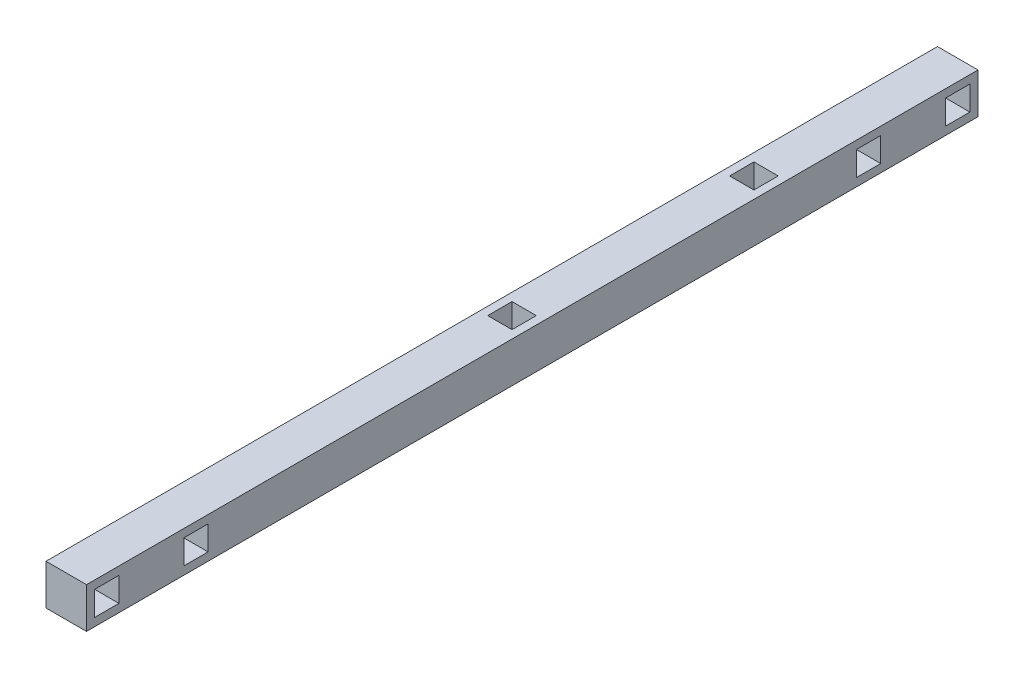
SolidWorks part; units mm, degrees
ref_plane "Front Plane" through (0, 0, 0) normal (0, 0, 1) x (1, 0, 0)
ref_plane "Top Plane" through (0, 0, 0) normal (0, 1, 0) x (1, 0, 0)
ref_plane "Right Plane" through (0, 0, 0) normal (1, 0, 0) x (0, 0, -1)
sketch "Sketch1" plane through (0, 0, 0) normal (0, 0, 1) x (1, 0, 0)
  line L1 (0, 0) -> (5, 0)
  line L2 (0, 0) -> (0, 5)
  line L3 (0, 5) -> (5, 5)
  line L4 (5, 0) -> (5, 5)
  dimension "D1" = 5
  dimension "D2" = 5
extrude "Boss-Extrude1" add sketch "Sketch1" along normal blind 110
sketch "Sketch2" plane through (0, 0, 0) normal (-1, 0, 0) x (0, 0, 1)
  line L0 (0, 5) -> (0, 0) construction
  line L1 (1, 1) -> (4, 1)
  line L2 (1, 1) -> (1, 4)
  line L3 (1, 4) -> (4, 4)
  line L4 (4, 1) -> (4, 4)
  line L5 (110, 5) -> (0, 5) construction
  line L6 (110, 5) -> (110, 0) construction
  line L7 (109, 4) -> (106, 4)
  line L8 (109, 4) -> (109, 1)
  line L9 (109, 1) -> (106, 1)
  line L10 (106, 4) -> (106, 1)
  line L12 (12, 4) -> (15, 4)
  line L13 (12, 4) -> (12, 1)
  line L14 (12, 1) -> (15, 1)
  line L15 (15, 4) -> (15, 1)
  line L16 (98, 4) -> (95, 4)
  line L17 (98, 4) -> (98, 1)
  line L18 (98, 1) -> (95, 1)
  line L19 (95, 4) -> (95, 1)
  dimension "D1" = 3
  dimension "D2" = 3
  dimension "D3" = 1
  dimension "D4" = 1
  dimension "D5" = 3
  dimension "D6" = 3
  dimension "D7" = 1
  dimension "D8" = 1
  dimension "D9" = 3
  dimension "D10" = 3
  dimension "D11" = 1
  dimension "D12" = 3
  dimension "D13" = 3
  dimension "D14" = 1
  dimension "D15" = 12
  dimension "D16" = 12
extrude "Cut-Extrude1" cut sketch "Sketch2" against normal blind 9
sketch "Sketch3" plane through (0, 5, 0) normal (0, 1, 0) x (1, 0, 0)
  line L0 (0, -110) -> (0, 0) construction
  line L1 (1, -23.65) -> (4, -23.65)
  line L2 (1, -23.65) -> (1, -26.65)
  line L3 (1, -26.65) -> (4, -26.65)
  line L4 (4, -23.65) -> (4, -26.65)
  line L5 (1, -26.65) -> (4, -23.65) construction
  line L6 (1, -23.65) -> (4, -26.65) construction
  line L7 (5, 0) -> (0, 0) construction
  line L9 (1, -53.5) -> (4, -53.5)
  line L10 (1, -53.5) -> (1, -56.5)
  line L11 (1, -56.5) -> (4, -56.5)
  line L12 (4, -53.5) -> (4, -56.5)
  point P6 (2.5, -25.15)
  dimension "D1" = 3
  dimension "D2" = 3
  dimension "D3" = 1
  dimension "D4" = 4.2426
  dimension "D5" = 4.2426
  dimension "D6" = 25.15
  dimension "D7" = 3
  dimension "D8" = 3
  dimension "D9" = 1
  dimension "D10" = 53.5
extrude "Cut-Extrude2" cut sketch "Sketch3" against normal blind 9
